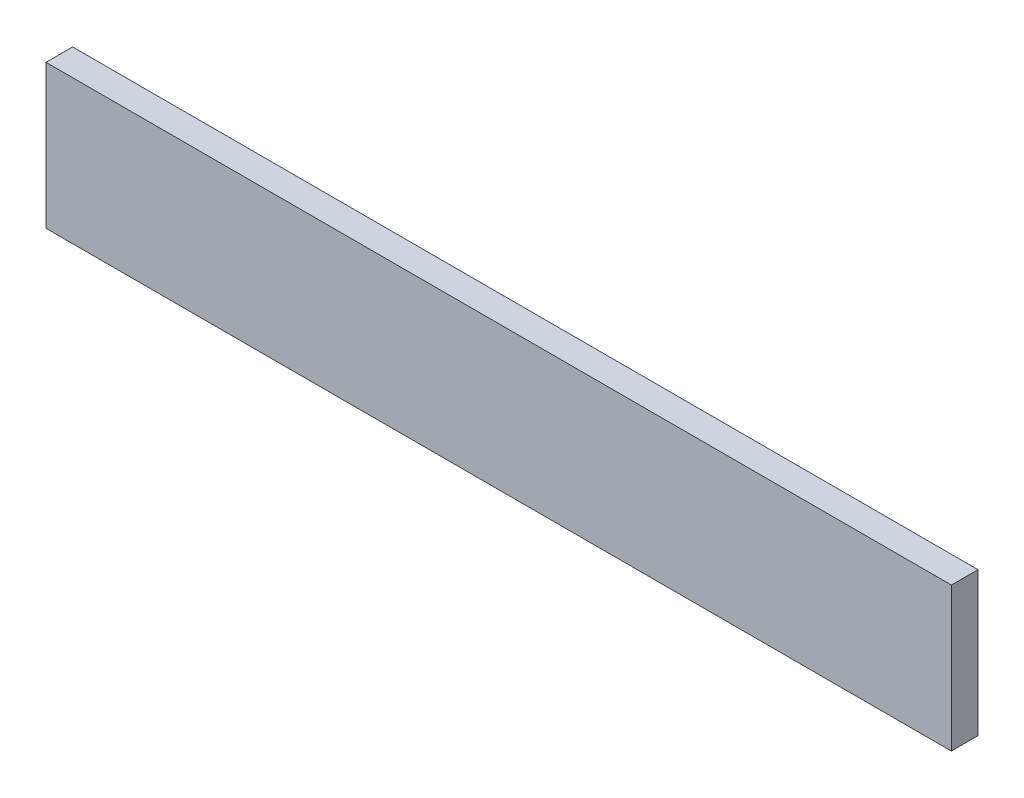
SolidWorks part; units mm, degrees
ref_plane "Front Plane" through (0, 0, 0) normal (0, 0, 1) x (1, 0, 0)
ref_plane "Top Plane" through (0, 0, 0) normal (0, 1, 0) x (1, 0, 0)
ref_plane "Right Plane" through (0, 0, 0) normal (1, 0, 0) x (0, 0, -1)
sketch "Sketch1" plane through (0, 0, 0) normal (0, 1, 0) x (1, 0, 0)
  line L1 (0, 0) -> (170, 0)
  line L2 (0, 0) -> (0, 5)
  line L3 (0, 5) -> (170, 5)
  line L4 (170, 0) -> (170, 5)
  dimension "D1" = 170
  dimension "D2" = 5
extrude "Boss-Extrude1" add sketch "Sketch1" along normal blind 27
